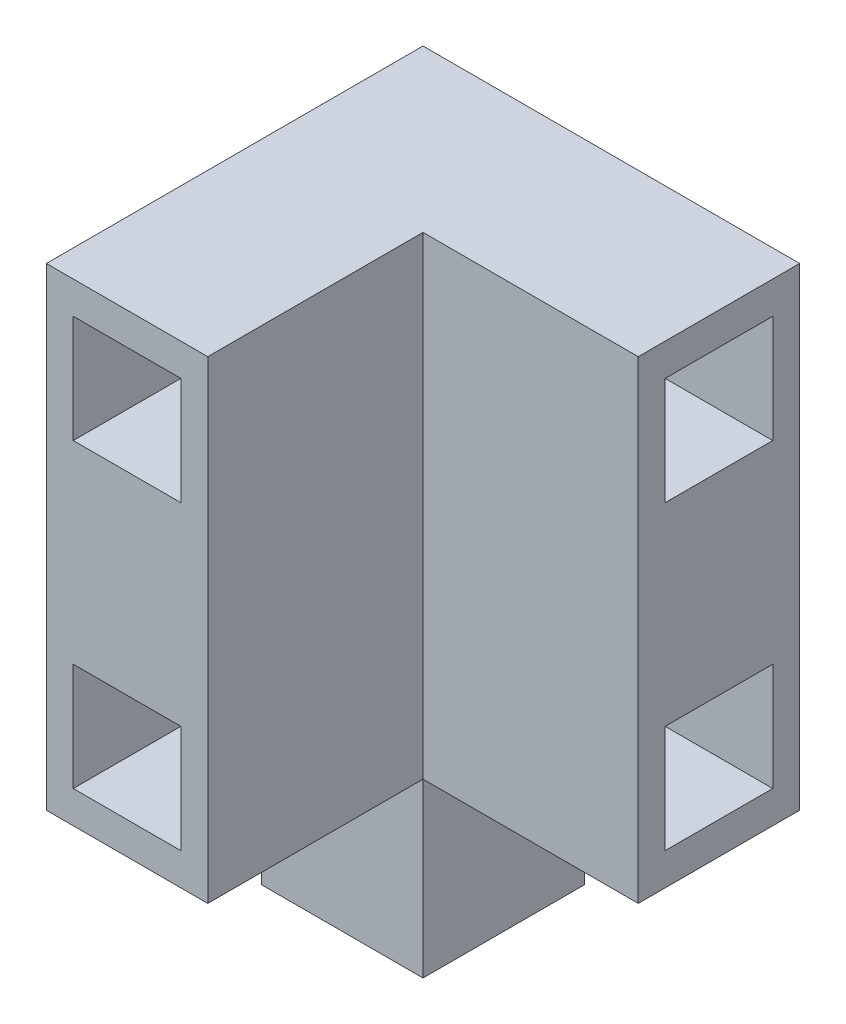
SolidWorks part; units mm, degrees
ref_plane "前视基准面" through (0, 0, 0) normal (0, 0, 1) x (1, 0, 0)
ref_plane "上视基准面" through (0, 0, 0) normal (0, 1, 0) x (1, 0, 0)
ref_plane "右视基准面" through (0, 0, 0) normal (1, 0, 0) x (0, 0, -1)
sketch "草图1" plane through (0, 0, 0) normal (0, 1, 0) x (1, 0, 0)
  line L1 (-7.5, 7.5) -> (7.5, 7.5)
  line L2 (-7.5, 7.5) -> (-7.5, -7.5)
  line L3 (-7.5, -7.5) -> (7.5, -7.5)
  line L4 (7.5, 7.5) -> (7.5, -7.5)
  line L5 (-7.5, 7.5) -> (7.5, -7.5) construction
  line L6 (-7.5, -7.5) -> (7.5, 7.5) construction
  point P0 (0, 0)
  dimension "D1" = 15
  dimension "D2" = 15
extrude "凸台-拉伸1" add sketch "草图1" along normal blind 60
sketch "草图4" plane through (0, 0, 7.5) normal (0, 0, 1) x (1, 0, 0)
  line L0 (7.5, 60) -> (7.5, 0) construction
  line L1 (-7.5, 60) -> (7.5, 60)
  line L2 (-7.5, 60) -> (-7.5, 16)
  line L3 (-7.5, 16) -> (7.5, 16)
  line L4 (7.5, 60) -> (7.5, 16)
  dimension "D1" = 44
extrude "凸台-拉伸4" add sketch "草图4" along normal blind 20
sketch "草图5" plane through (7.5, 0, 0) normal (1, 0, 0) x (0, 0, -1)
  line L1 (7.5, 60) -> (-7.5, 60)
  line L2 (7.5, 60) -> (7.5, 16)
  line L3 (7.5, 16) -> (-7.5, 16)
  line L4 (-7.5, 60) -> (-7.5, 16)
extrude "凸台-拉伸5" add sketch "草图5" along normal blind 20
sketch "草图6" plane through (0, 0, 27.5) normal (0, 0, 1) x (1, 0, 0)
  line L0 (7.5, 60) -> (-7.5, 60) construction
  line L1 (-5, 47) -> (5, 47)
  line L2 (-5, 47) -> (-5, 57)
  line L3 (-5, 57) -> (5, 57)
  line L4 (5, 47) -> (5, 57)
  line L5 (-5, 47) -> (5, 57) construction
  line L6 (-5, 57) -> (5, 47) construction
  line L7 (-7.5, 16) -> (7.5, 16) construction
  line L8 (-5, 19) -> (5, 19)
  line L9 (-5, 19) -> (-5, 29)
  line L10 (-5, 29) -> (5, 29)
  line L11 (5, 19) -> (5, 29)
  line L12 (-5, 19) -> (5, 29) construction
  line L13 (-5, 29) -> (5, 19) construction
  point P0 (0, 52)
  point P9 (0, 24)
  dimension "D1" = 10
  dimension "D2" = 10
  dimension "D3" = 3
  dimension "D4" = 10
  dimension "D5" = 10
  dimension "D6" = 3
extrude "切除-拉伸1" cut sketch "草图6" against normal blind 70
sketch "草图7" plane through (27.5, 0, 0) normal (1, 0, 0) x (0, 0, -1)
  line L0 (7.5, 60) -> (-7.5, 60) construction
  line L1 (-5, 57) -> (5, 57)
  line L2 (-5, 57) -> (-5, 47)
  line L3 (-5, 47) -> (5, 47)
  line L4 (5, 57) -> (5, 47)
  line L5 (-5, 57) -> (5, 47) construction
  line L6 (-5, 47) -> (5, 57) construction
  line L7 (-7.5, 16) -> (7.5, 16) construction
  line L8 (-5, 29) -> (5, 29)
  line L9 (-5, 29) -> (-5, 19)
  line L10 (-5, 19) -> (5, 19)
  line L11 (5, 29) -> (5, 19)
  line L12 (-5, 29) -> (5, 19) construction
  line L13 (-5, 19) -> (5, 29) construction
  point P0 (0, 52)
  point P8 (0, 24)
  dimension "D1" = 10
  dimension "D2" = 10
  dimension "D3" = 3
  dimension "D4" = 10
  dimension "D5" = 10
  dimension "D6" = 3
extrude "切除-拉伸2" cut sketch "草图7" against normal blind 70
